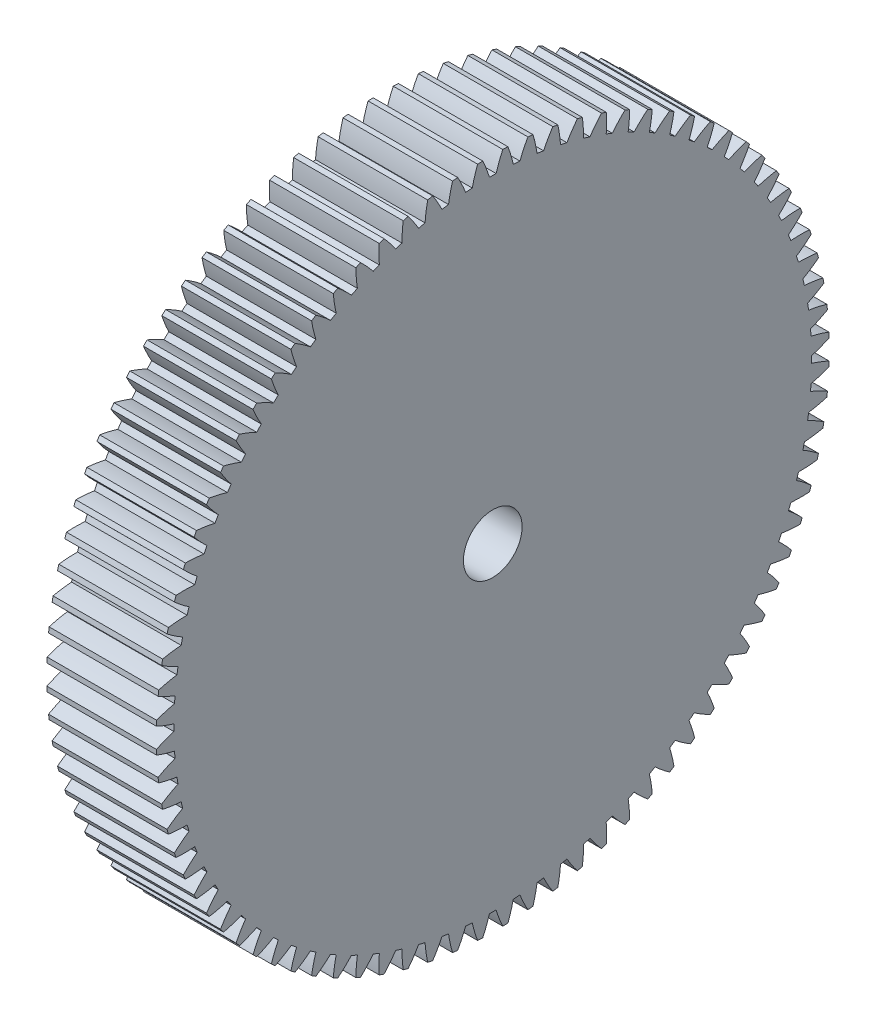
SolidWorks part; units mm, degrees
ref_plane "Plane1" through (0, 0, 0) normal (0, 0, 1) x (1, 0, 0)
ref_plane "Plane2" through (0, 0, 0) normal (0, 1, 0) x (1, 0, 0)
ref_plane "Plane3" through (0, 0, 0) normal (1, 0, 0) x (0, 0, -1)
sketch "HoldingSke" plane through (0, 0, 0) normal (0, 1, 0) x (1, 0, 0)
  line L0 (0, 0) -> (15.9301, -151.5651)
  line L1 (-15, 0) -> (100, 0) construction
  line L2 (0, 0) -> (-2.1039, 2.3779)
  line L3 (0, 0) -> (-11.863, 4.5341)
  line L4 (0, 0) -> (0.9027, 8.5887)
  line L5 (0, 0) -> (-47.5972, -17.7524)
  line L6 (0, 0) -> (-49.1299, -33.1481)
  line L7 (-2.1039, 2.3779) -> (10.6533, 60.2555)
  line L8 (-76.2, 54.61) -> (-41.4782, 54.61)
  line L9 (-71.009, 38.7566) -> (-53.1078, 45.2721)
  line L10 (-76.2, 71.12) -> (104.1128, 71.12)
  line L11 (0, 0) -> (-59.2667, 0)
  line L12 (-76.2, 101.6) -> (-76.0298, 101.6)
  line L13 (24.9733, 27.94) -> (52.9518, 28.4284)
  line L14 (24.9733, 27.94) -> (24.9746, 27.94)
  line L15 (24.9733, 27.94) -> (100.4006, 29.5858)
  circle A0 centre (0, 0) radius 15.875
  circle A1 centre (0, 0) radius 38.1
  circle A2 centre (0, 0) radius 38.1
  circle A3 centre (0, 0) radius 15.875
  dimension "MHD" = 76.2
  dimension "Hub_dia" = 76.2
  dimension "Bore" = 31.75
  dimension "MBD" = 31.75
  dimension "Num_teeth" = 84
  dimension "Pitch" = 152.4
  dimension "Overall_len" = 50.8
  dimension "Show_teeth" = 84
  dimension "Thickness" = 59.2667
  dimension "OAL" = 59.2669
  dimension "T_dim" = 34.7218
  dimension "Ap" = 20
  dimension "H" = 19.05
  dimension "Pitch_radius" = 180.3128
  dimension "Width" = 59.2667
  dimension "Backlash" = 0.1702
  dimension "Addendum_fac" = 1
  dimension "Dedendum_fac" = 1.25
  dimension "Clearance_fac" = 0.25
  dimension "Dedendum_add" = 0.0013
sketch "BasProSke" plane through (0, 0, 0) normal (0, 1, 0) x (1, 0, 0)
  line L0 (-10, 0) -> (60, 0) construction
  line L1 (0, 0) -> (0, 182.0333)
  line L2 (0, 0) -> (59.2667, 0)
  line L3 (59.2667, 0) -> (59.2667, 182.0333)
  line L4 (59.2667, 182.0333) -> (0, 182.0333)
  dimension "Thickness" = 59.2667
  dimension "Diameter" = 364.0667
revolve "Base-Revolve" add sketch "BasProSke" angle 360 about L0
sketch "TooCutSke" plane through (0, 0, 0) normal (1, 0, 0) x (0, 0, -1)
  line L1 (0, 0) -> (0, 107) construction
  line L2 (0, 0) -> (-3.6225, 177.7631) construction
  line L3 (0, 0) -> (-13.2944, 355.2998) construction
  line L4 (-3.6225, 177.7631) -> (-6.6472, 177.6499) construction
  arc A0 (1.7912, 172.4978) -> (-1.7912, 172.4978) centre (0, 0) ccw
  arc A1 (5.4351, 181.9776) -> (-5.4351, 181.9776) centre (0, 0) ccw
  circle A2 centre (0, 0) radius 177.8 construction
  circle A3 centre (0, 0) radius 167.0773 construction
  arc A4 (-1.7912, 172.4978) -> (-5.4351, 181.9776) centre (-69.8284, 151.7855) ccw
  arc A5 (5.4351, 181.9776) -> (1.7912, 172.4978) centre (69.8284, 151.7855) ccw
  dimension "Root_dia" = 345.0141
  dimension "Overcut_dia" = 364.1175
  dimension "Pitch_dia" = 355.6
  dimension "Base_dia" = 334.1547
  dimension "Flank_rad" = 71.12
  dimension "Half_ang" = 2.143
  dimension "Half_CT" = 3.0268
extrude "ToothCut" cut sketch "TooCutSke" along normal through all
fillet "Breaks" [suppressed] radius 0.0847
fillet "RootFillets" [suppressed] radius 1.0596
pattern_circular "TeethCuts" count 84 every 4.286 about axis through (-10, 0, 0) along (1, 0, 0) of "ToothCut", "RootFillets", "Breaks"
sketch "HubNeaOneSke" plane through (0, 0, 0) normal (-1, 0, 0) x (0, 0, 1)
  circle A0 centre (0, 0) radius 38.1
  dimension "Diameter" = 76.2
extrude "HubNearOne" [suppressed] add sketch "HubNeaOneSke" along normal blind 0.0002
sketch "HubNeaBotSke" plane through (0, 0, 0) normal (-1, 0, 0) x (0, 0, 1)
  circle A0 centre (0, 0) radius 38.1
  dimension "Diameter" = 76.2
extrude "HubNearBoth" [suppressed] add sketch "HubNeaBotSke" along normal blind 0.0001
ref_plane "FarPln" through (59.2667, 0, 0) normal (1, 0, 0) x (0, 0, -1)
sketch "HubFarSke" plane through (59.2667, 0, 0) normal (1, 0, 0) x (0, 0, -1)
  circle A0 centre (0, 0) radius 38.1
  dimension "Diameter" = 76.2
extrude "HubFar" [suppressed] add sketch "HubFarSke" along normal blind 0.0001
sketch "BorSke" plane through (0, 0, 0) normal (1, 0, 0) x (0, 0, -1)
  circle A0 centre (0, 0) radius 15.875
  dimension "Diameter" = 31.75
extrude "Bore" cut sketch "BorSke" along normal mid plane 118.5337
equation "' \"Pitch@HoldingSke\" = 4"
equation "' \"Num_teeth@HoldingSke\" = 12"
equation "' \"Ap@HoldingSke\" =  20"
equation "' \"Ap@HoldingSke\" = 20"
equation "' \"Width@HoldingSke\" = 0.5"
equation "' \"Hub_dia@HoldingSke\"= 1"
equation "' \"Hub_dia@HoldingSke\" = 1"
equation "' \"Overall_len@HoldingSke\" = 1.0"
equation "' \"Bore@HoldingSke\" = 0.75"
equation "' \"T_dim@HoldingSke\" = 0.85"
equation "' \"Width@KeySke\" = 0.25"
equation "' \"Show_teeth@HoldingSke\" = 13"
equation "' \"Backlash@HoldingSke\" = 0.009"
equation "' \"Addendum_fac@HoldingSke\" = 1.0"
equation "' \"Dedendum_fac@HoldingSke\" = 1.25"
equation "' \"Dedendum_add@HoldingSke\" = 0.00005"
equation "' \"Clearance_fac@HoldingSke\" = 0.25"
equation "' \"Pitch@HoldingSke\" = 0.5"
equation "' \"Num_teeth@HoldingSke\" = 23"
equation "' \"Show_teeth@HoldingSke\" = 23"
equation "' \"Backlash@HoldingSke\" = 0.0375"
equation "\"Overcut_dia@TooCutSke\" = (\"Num_teeth@HoldingSke\" + 2 * \"Addendum_fac@HoldingSke\") / \"Pitch@HoldingSke\" + 0.002"
equation "\"Pitch_dia@TooCutSke\" = \"Num_teeth@HoldingSke\" / \"Pitch@HoldingSke\""
equation "\"Base_dia@TooCutSke\" = \"Num_teeth@HoldingSke\" / \"Pitch@HoldingSke\" * cos((\"Ap@HoldingSke\"  * 3.14159265 / 180))"
equation "\"Root_dia@TooCutSke\" = (\"Num_teeth@HoldingSke\" + 2) / \"Pitch@HoldingSke\" - 2 * (\"Addendum_fac@HoldingSke\" + \"Dedendum_fac@HoldingSke\") / \"Pitch@HoldingSke\" - \"Dedendum_add@HoldingSke\" * 2"
equation "\"Half_ang@TooCutSke\" = 180 / \"Num_teeth@HoldingSke\""
equation "\"Half_CT@TooCutSke\" = \"Num_teeth@HoldingSke\" / \"Pitch@HoldingSke\" * sin((3.14159265 / 2 / \"Num_teeth@HoldingSke\")) / 2 - 7 * \"Backlash@HoldingSke\" / 4"
equation "\"Flank_rad@TooCutSke\" = \"Num_teeth@HoldingSke\" / \"Pitch@HoldingSke\" / 5"
equation "\"Radius@RootFillets\" = \"Clearance_fac@HoldingSke\" / \"Pitch@HoldingSke\" + \"Dedendum_add@HoldingSke\""
equation "\"Break_rad@Breaks\" = 0.02 / \"Pitch@HoldingSke\""
equation "\"Thickness@HoldingSke\" = \"Width@HoldingSke\""
equation "\"OAL@HoldingSke\" = \"Thickness@HoldingSke\""
equation "\"MHD@HoldingSke\" = (\"Num_teeth@HoldingSke\" + 2) / \"Pitch@HoldingSke\" - 2 * (\"Addendum_fac@HoldingSke\" + \"Dedendum_fac@HoldingSke\")  / \"Pitch@HoldingSke\" - \"Dedendum_add@HoldingSke\" * 2"
equation "\"MBD@HoldingSke\" = (\"Num_teeth@HoldingSke\" + 2) / \"Pitch@HoldingSke\" - 2 * (\"Addendum_fac@HoldingSke\" + \"Dedendum_fac@HoldingSke\")  / \"Pitch@HoldingSke\" - \"Dedendum_add@HoldingSke\" * 2 - 0.002"
equation "\"MHD@HoldingSke\" = ((sgn( \"MHD@HoldingSke\" - \"Hub_dia@HoldingSke\" )-1)*( \"MHD@HoldingSke\" - \"Hub_dia@HoldingSke\" ))/-2+ \"Hub_dia@HoldingSke\""
equation "\"MBD@HoldingSke\" = ((sgn( \"MBD@HoldingSke\" - \"Bore@HoldingSke\" )-1)*( \"MBD@HoldingSke\" - \"Bore@HoldingSke\" ))/-2+ \"Bore@HoldingSke\""
equation "\"OAL@HoldingSke\" = ((sgn( \"OAL@HoldingSke\" - \"Overall_len@HoldingSke\" )+1)*( \"OAL@HoldingSke\" - \"Overall_len@HoldingSke\" ))/2 + \"Overall_len@HoldingSke\" + 0.000002"
equation "\"Num_teeth@TeethCuts\" = int( \"Show_teeth@HoldingSke\" ) + 1"
equation "\"Num_teeth@TeethCuts\" = ((sgn( \"Num_teeth@TeethCuts\" - \"Num_teeth@HoldingSke\" )-1)*( \"Num_teeth@TeethCuts\" - \"Num_teeth@HoldingSke\" ))/-2+ \"Num_teeth@HoldingSke\""
equation "\"Num_teeth@TeethCuts\" = ((sgn( \"Num_teeth@TeethCuts\" - 2.0)+1)*( \"Num_teeth@TeethCuts\" - 2.0))/2 +2.0"
equation "\"Angle@TeethCuts\" = 360.0 / \"Num_teeth@HoldingSke\""
equation "\"Diameter@BasProSke\" = (\"Num_teeth@HoldingSke\" + 2 * \"Addendum_fac@HoldingSke\") / \"Pitch@HoldingSke\""
equation "\"Thickness@BasProSke\"  = \"Thickness@HoldingSke\""
equation "' \"Fillet_rad@BasProSke\" =  \"Thickness@HoldingSke\" * 0.05"
equation "' \"Fillet_rad@BasProSke\" = \"Thickness@HoldingSke\" * 0.05"
equation "\"MHD@HoldingSke\" = ((sgn( \"MHD@HoldingSke\" - \"Root_dia@TooCutSke\" )-1)*( \"MHD@HoldingSke\" - \"Root_dia@TooCutSke\" ))/-2+ \"Root_dia@TooCutSke\""
equation "\"Diameter@HubNeaOneSke\" = \"MHD@HoldingSke\""
equation "\"Length@HubNearOne\" = \"OAL@HoldingSke\" - \"Thickness@BasProSke\""
equation "\"Diameter@HubNeaBotSke\" = \"MHD@HoldingSke\""
equation "\"Length@HubNearBoth\" = ( \"OAL@HoldingSke\" - \"Thickness@BasProSke\" ) / 2.0"
equation "\"Thickness@FarPln\" = \"Thickness@BasProSke\""
equation "\"Diameter@HubFarSke\" = \"MHD@HoldingSke\""
equation "\"Length@HubFar\" = ( \"OAL@HoldingSke\" - \"Thickness@BasProSke\" ) / 2.0"
equation "\"Diameter@BorSke\" = \"MBD@HoldingSke\""
equation "\"D1@Bore\" = \"OAL@HoldingSke\" * 2.0"
